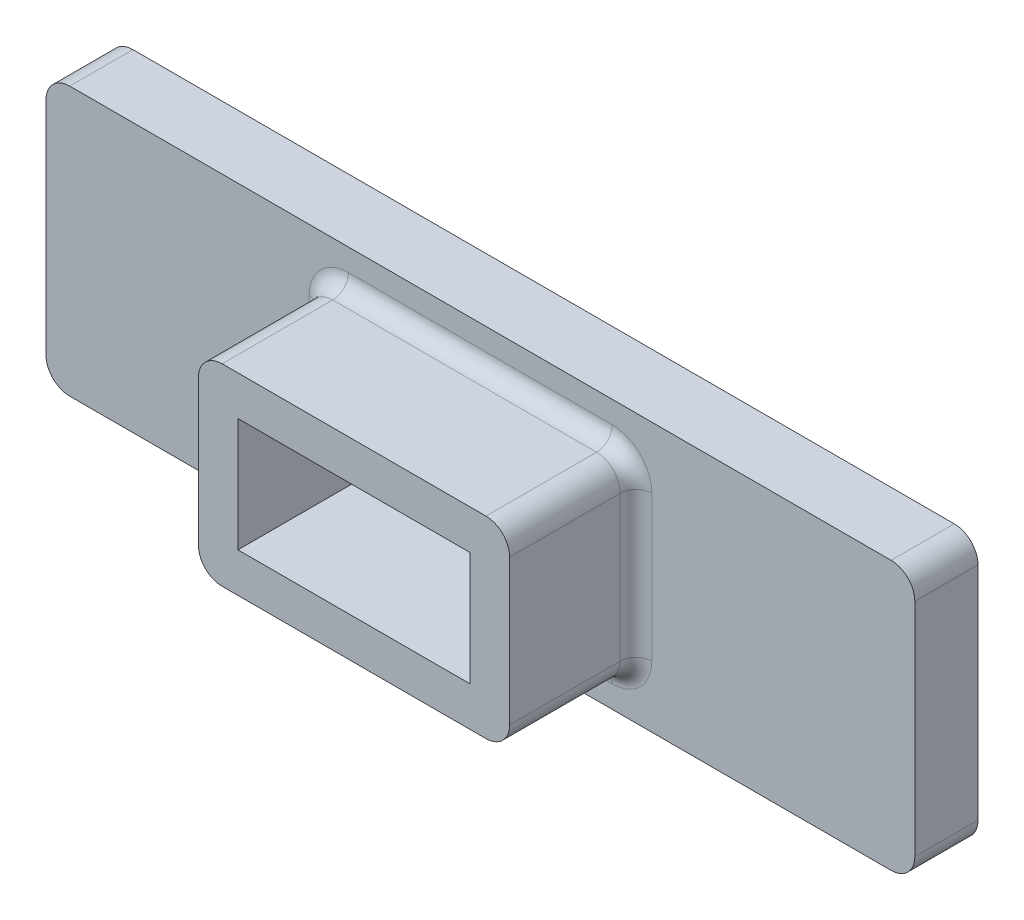
SolidWorks part; units mm, degrees
material "PLA2"
ref_plane "Front Plane" through (0, 0, 0) normal (0, 0, 1) x (1, 0, 0)
ref_plane "Top Plane" through (0, 0, 0) normal (0, 1, 0) x (1, 0, 0)
ref_plane "Right Plane" through (0, 0, 0) normal (1, 0, 0) x (0, 0, -1)
sketch "Sketch1" plane through (0, 0, 0) normal (0, 0, 1) x (1, 0, 0)
  line L1 (-34.925, 10.795) -> (34.925, 10.795)
  line L2 (-34.925, 10.795) -> (-34.925, -10.795)
  line L3 (-34.925, -10.795) -> (34.925, -10.795)
  line L4 (34.925, 10.795) -> (34.925, -10.795)
  line L5 (-34.925, 10.795) -> (34.925, -10.795) construction
  line L6 (-34.925, -10.795) -> (34.925, 10.795) construction
  point P0 (0, 0)
  dimension "D1" = 69.85
  dimension "D2" = 21.59
extrude "Boss-Extrude1" add sketch "Sketch1" along normal blind 5.08
sketch "Sketch2" plane through (0, 0, 5.08) normal (0, 0, 1) x (1, 0, 0)
  line L1 (-12.5095, 7.747) -> (12.5095, 7.747)
  line L2 (-12.5095, 7.747) -> (-12.5095, -7.747)
  line L3 (-12.5095, -7.747) -> (12.5095, -7.747)
  line L4 (12.5095, 7.747) -> (12.5095, -7.747)
  line L5 (-12.5095, 7.747) -> (12.5095, -7.747) construction
  line L6 (-12.5095, -7.747) -> (12.5095, 7.747) construction
  line L7 (-9.3345, 4.572) -> (9.3345, 4.572)
  line L8 (-9.3345, 4.572) -> (-9.3345, -4.572)
  line L9 (-9.3345, -4.572) -> (9.3345, -4.572)
  line L10 (9.3345, 4.572) -> (9.3345, -4.572)
  line L11 (-9.3345, 4.572) -> (9.3345, -4.572) construction
  line L12 (-9.3345, -4.572) -> (9.3345, 4.572) construction
  line L13 (-9.2075, 4.445) -> (9.2075, 4.445) construction
  line L14 (-9.2075, 4.445) -> (-9.2075, -4.445) construction
  line L15 (-9.2075, -4.445) -> (9.2075, -4.445) construction
  line L16 (9.2075, 4.445) -> (9.2075, -4.445) construction
  line L17 (-9.2075, 4.445) -> (9.2075, -4.445) construction
  line L18 (-9.2075, -4.445) -> (9.2075, 4.445) construction
  point P0 (0, 0)
  point P6 (0, 0)
  point P11 (0, 0)
  dimension "D1" = 3.175
  dimension "D2" = 3.175
  dimension "D3" = 8.89
  dimension "D4" = 18.415
  dimension "D5" = 0.127
  dimension "D6" = 0.127
extrude "Boss-Extrude2" add sketch "Sketch2" along normal blind 10.16
fillet "Fillet2" radius 1.905 8 edges at (-12.5095, 7.747, 10.16) (12.5095, 7.747, 10.16) (12.5095, -7.747, 10.16) (-12.5095, -7.747, 10.16) (34.925, 10.795, 2.54) (34.925, -10.795, 2.54) (-34.925, 10.795, 2.54) (-34.925, -10.795, 2.54)
fillet "Fillet3" radius 1.27 8 edges at (-11.9515, -7.189, 5.08) (-12.5095, 0, 5.08) (-11.9515, 7.189, 5.08) (0, 7.747, 5.08) (11.9515, 7.189, 5.08) (12.5095, 0, 5.08) (11.9515, -7.189, 5.08) (0, -7.747, 5.08)
